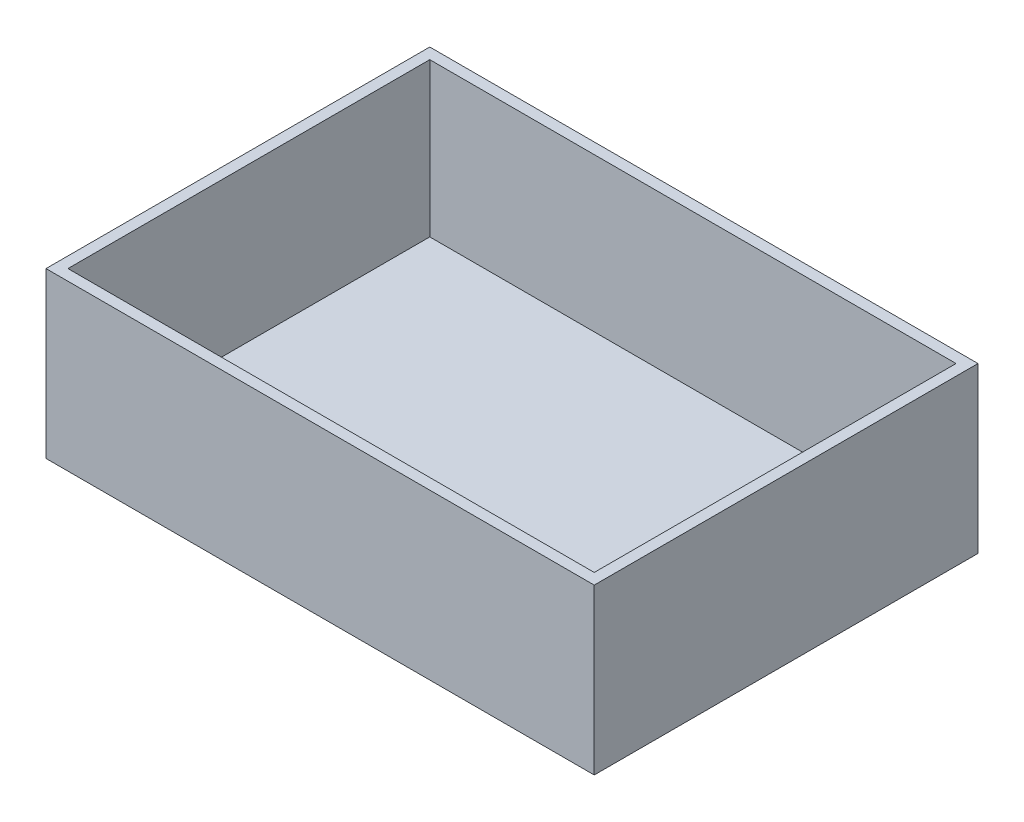
SolidWorks part; units mm, degrees
ref_plane "Alzado" through (0, 0, 0) normal (0, 0, 1) x (1, 0, 0)
ref_plane "Planta" through (0, 0, 0) normal (0, 1, 0) x (1, 0, 0)
ref_plane "Vista lateral" through (0, 0, 0) normal (1, 0, 0) x (0, 0, -1)
sketch "Croquis1" plane through (0, 0, 0) normal (0, 1, 0) x (1, 0, 0)
  line L1 (50, -35) -> (-50, -35)
  line L2 (50, -35) -> (50, 35)
  line L3 (50, 35) -> (-50, 35)
  line L4 (-50, -35) -> (-50, 35)
  line L5 (50, -35) -> (-50, 35) construction
  line L6 (50, 35) -> (-50, -35) construction
  point P0 (0, 0)
  dimension "D1" = 100
  dimension "D2" = 70
extrude "Saliente-Extruir1" add sketch "Croquis1" along normal blind 30
shell "Vaciado1" thickness 2
